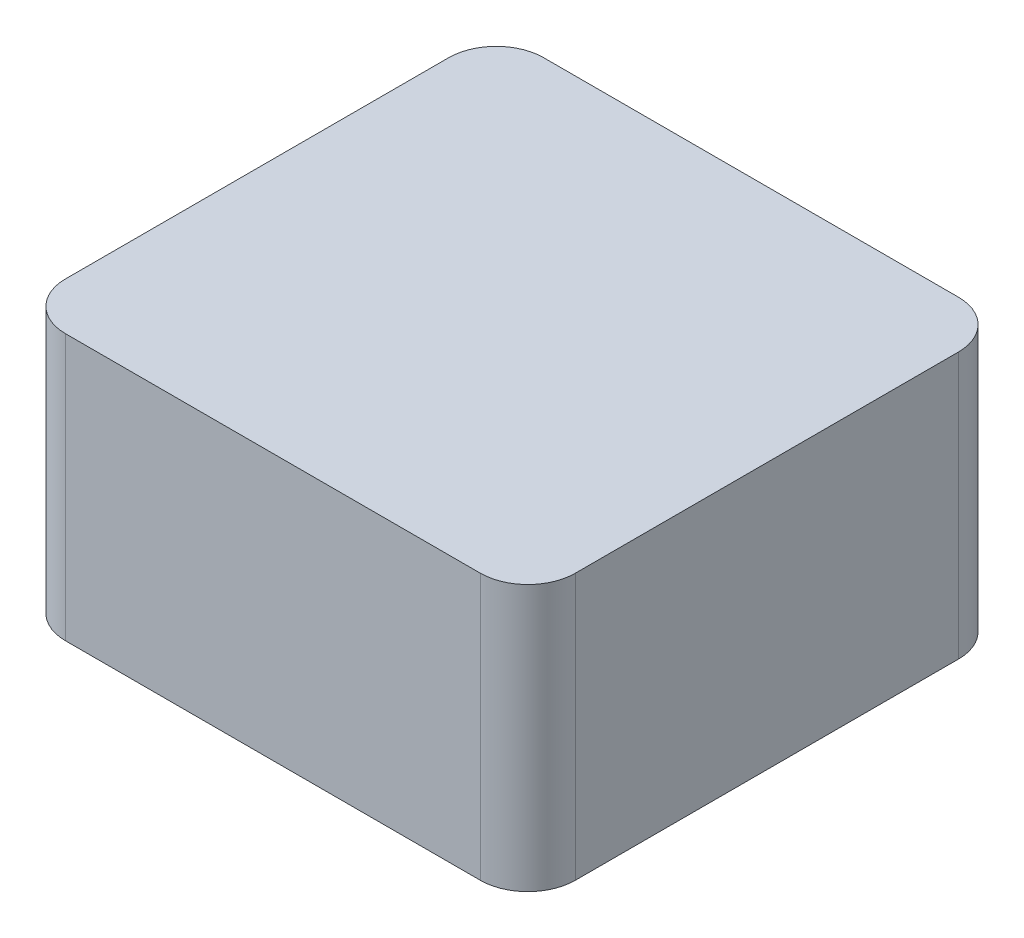
SolidWorks part; units mm, degrees
ref_plane "Front Plane" through (0, 0, 0) normal (0, 0, 1) x (1, 0, 0)
ref_plane "Top Plane" through (0, 0, 0) normal (0, 1, 0) x (1, 0, 0)
ref_plane "Right Plane" through (0, 0, 0) normal (1, 0, 0) x (0, 0, -1)
sketch "Sketch1" plane through (0, 0, 0) normal (0, 1, 0) x (1, 0, 0)
  line L1 (0, 0) -> (40.894, 0)
  line L2 (0, 0) -> (0, -38.354)
  line L3 (0, -38.354) -> (40.894, -38.354)
  line L4 (40.894, 0) -> (40.894, -38.354)
  dimension "D1" = 38.354
  dimension "D2" = 40.894
extrude "Boss-Extrude1" add sketch "Sketch1" along normal blind 21.336
fillet "Fillet1" radius 3.81 4 edges at (0, 10.668, 0) (40.894, 10.668, 0) (40.894, 10.668, 38.354) (0, 10.668, 38.354)
